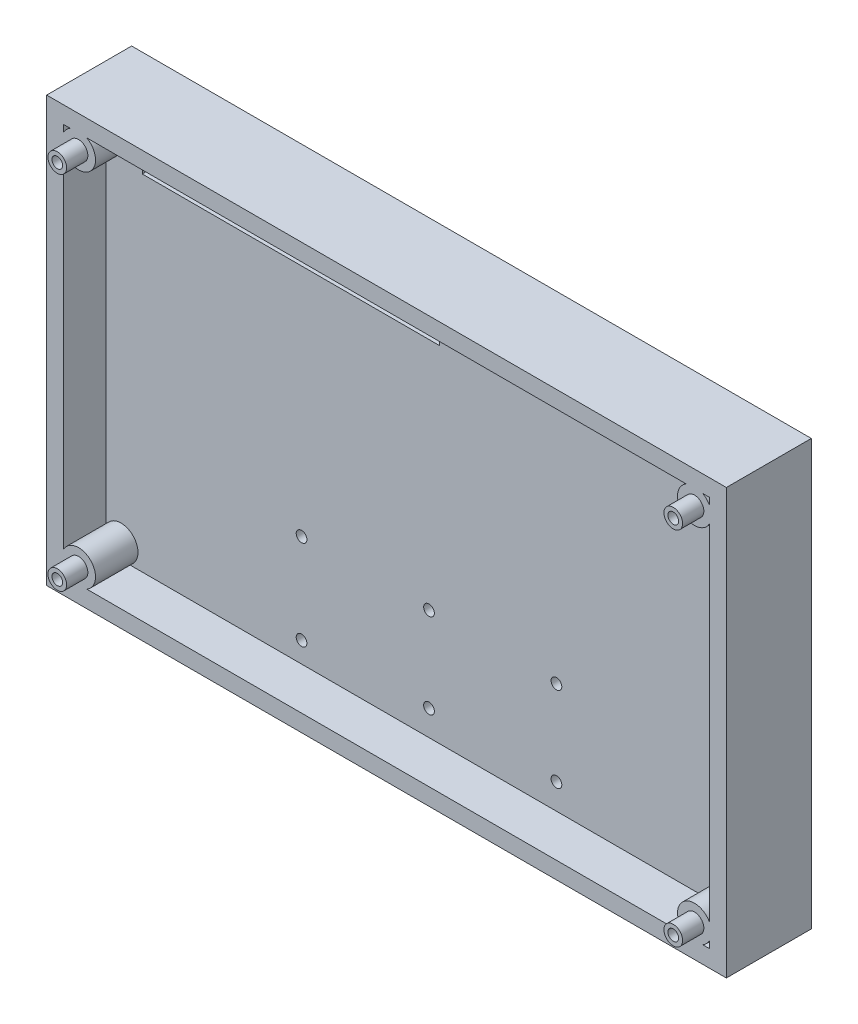
SolidWorks part; units mm, degrees
ref_plane "Front Plane" through (0, 0, 0) normal (0, 0, 1) x (1, 0, 0)
ref_plane "Top Plane" through (0, 0, 0) normal (0, 1, 0) x (1, 0, 0)
ref_plane "Right Plane" through (0, 0, 0) normal (1, 0, 0) x (0, 0, -1)
sketch "Sketch2" plane through (0, 0, 0) normal (0, 0, 1) x (1, 0, 0)
  line L1 (0, 0) -> (101.6, 0)
  line L2 (0, 0) -> (0, 63.5)
  line L3 (0, 63.5) -> (101.6, 63.5)
  line L4 (101.6, 0) -> (101.6, 63.5)
  dimension "D1" = 101.6
  dimension "D2" = 63.5
extrude "Boss-Extrude1" add sketch "Sketch2" along normal blind 6.35
sketch "Sketch3" plane through (0, 0, 6.35) normal (0, 0, 1) x (1, 0, 0)
  line L0 (0, 0) -> (101.6, 0) construction
  line L1 (0, 63.5) -> (0, 0) construction
  circle A0 centre (4.7625, 4.7625) radius 2.54
  circle A1 centre (96.8375, 4.7625) radius 2.54
  circle A2 centre (96.8375, 58.7375) radius 2.54
  circle A3 centre (4.7625, 58.7375) radius 2.54
  dimension "D1" = 92.075
  dimension "D3" = 0
  dimension "D4" = 53.975
  dimension "D5" = 4.7625
  dimension "D7" = 5.08
  dimension "D2" = 92.075
  dimension "D6" = 4.7625
extrude "Boss-Extrude2" add sketch "Sketch3" along normal blind 6.35
sketch "Sketch4" plane through (0, 0, 12.7) normal (0, 0, 1) x (1, 0, 0)
  circle A0 centre (4.7625, 58.7375) radius 1.397
  circle A1 centre (4.7625, 4.7625) radius 1.397
  circle A2 centre (96.8375, 58.7375) radius 1.397
  circle A3 centre (96.8375, 4.7625) radius 1.397
  dimension "D1" = 2.794
extrude "Boss-Extrude3" add sketch "Sketch4" along normal blind 3.175
hole_wizard "M2x0.4 Tapped Hole1" positions "Sketch5" profile "Sketch7" tap size "M2x0.4" standard "ANSI Metric"
sketch "Sketch5" plane through (0, 0, 15.875) normal (0, 0, 1) x (1, 0, 0)
  point P0 (4.7625, 58.7375)
  point P3 (4.7625, 4.7625)
  point P6 (96.8375, 58.7375)
  point P9 (96.8375, 4.7625)
sketch "Sketch7" plane through (4.7625, 58.7375, 15.875) normal (1, 0, 0) x (0, -1, 0)
  line L0 (0, 0) -> (0, 5.7447)
  line L1 (0, 5.7447) -> (0.8, 5.264)
  line L2 (0.8, 5.264) -> (0.8, 0)
  line L5 (0.8, 0) -> (0, 0)
  line L10 (0, 5.7447) -> (-0.8, 5.264) construction
  line L11 (0, -6.35) -> (0, 107.95) construction
  dimension "Tap Drill Dia." = 1.6
  dimension "Tap Drill Depth" = 5.264
  dimension "Drill Angle" = 118
cosmetic thread "Hole Thread1" parameters "D1"=4.064, "D2"=2
cosmetic thread "Hole Thread2" parameters "D1"=4.064, "D2"=2
cosmetic thread "Hole Thread3" parameters "D1"=4.064, "D2"=2
cosmetic thread "Hole Thread4" parameters "D1"=4.064, "D2"=2
sketch "Sketch8" plane through (0, 0, 6.35) normal (0, 0, 1) x (1, 0, 0)
  line L0 (101.6, 63.5) -> (0, 63.5) construction
  line L1 (7.9375, 60.4281) -> (52.3875, 60.4281)
  line L2 (7.9375, 60.4281) -> (7.9375, 54.0781)
  line L3 (7.9375, 54.0781) -> (52.3875, 54.0781)
  line L4 (52.3875, 60.4281) -> (52.3875, 54.0781)
  circle A0 centre (4.7625, 58.7375) radius 1.397 construction
  dimension "D1" = 44.45
  dimension "D2" = 6.35
  dimension "D3" = 3.175
  dimension "D4" = 3.0719
extrude "Cut-Extrude1" cut sketch "Sketch8" against normal blind 8.255
sketch3d "3DSketch1"
  line L0 (2.54, 2.54, 6.35) -> (99.06, 2.54, 6.35)
  line L1 (99.06, 2.54, 6.35) -> (99.06, 60.96, 6.35)
  line L2 (99.06, 60.96, 6.35) -> (2.54, 60.96, 6.35)
  line L3 (2.54, 60.96, 6.35) -> (2.54, 2.54, 6.35)
  line L4 (2.54, 2.54, 6.35) -> (99.06, 2.54, 6.35)
  line L5 (99.06, 2.54, 6.35) -> (99.06, 60.96, 6.35)
  line L6 (99.06, 60.96, 6.35) -> (2.54, 60.96, 6.35)
  line L7 (2.54, 60.96, 6.35) -> (2.54, 2.54, 6.35)
  line L9 (101.6, 0, 6.35) -> (101.6, 63.5, 6.35) construction
  line L10 (101.6, 63.5, 6.35) -> (0, 63.5, 6.35) construction
  line L11 (0, 0, 6.35) -> (101.6, 0, 6.35) construction
  line L12 (0, 63.5, 6.35) -> (0, 0, 6.35) construction
  line L13 (101.6, 0, 6.35) -> (101.6, 63.5, 6.35)
  line L14 (101.6, 63.5, 6.35) -> (0, 63.5, 6.35)
  line L15 (0, 0, 6.35) -> (101.6, 0, 6.35)
  line L16 (0, 63.5, 6.35) -> (0, 0, 6.35)
  dimension "D1" = 2.54
extrude "Boss-Extrude5" add sketch "3DSketch1" along direction (0, 0, -1) on the side against the normal blind 6.35
hole_wizard "M2x0.4 Tapped Hole2" positions "Sketch9" profile "Sketch10" tap size "M2x0.4" standard "ANSI Metric" end condition through all
sketch "Sketch9" plane through (0, 0, 0) normal (0, 0, -1) x (-1, 0, 0)
  line L0 (-101.6, 0) -> (-101.6, 63.5) construction
  line L1 (0, 0) -> (-101.6, 0) construction
  point P0 (-69.85, 19.05)
  point P2 (-50.8, 19.05)
  point P4 (-31.75, 19.05)
  point P6 (-69.85, 6.35)
  point P8 (-50.8, 6.35)
  point P10 (-31.75, 5.6205)
  dimension "D1" = 19.05
  dimension "D2" = 19.05
  dimension "D3" = 19.05
  dimension "D4" = 19.05
  dimension "D5" = 0
  dimension "D6" = 31.75
  dimension "D7" = 6.35
  dimension "D8" = 12.7
sketch "Sketch10" plane through (69.85, 19.05, 0) normal (1, 0, 0) x (0, 1, 0)
  line L0 (0, 0) -> (0, 15.875)
  line L1 (0, 15.875) -> (0.8, 15.875)
  line L2 (0.8, 15.875) -> (0.8, 0)
  line L5 (0.8, 0) -> (0, 0)
  line L11 (0, -6.35) -> (0, 107.95) construction
  dimension "Thru Tap Drill Dia." = 1.6
  dimension "Thru Tap Drill Depth" = 15.875
cosmetic thread "Hole Thread5" parameters "D2"=2
cosmetic thread "Hole Thread6" parameters "D2"=2
cosmetic thread "Hole Thread7" parameters "D2"=2
cosmetic thread "Hole Thread8" parameters "D2"=2
cosmetic thread "Hole Thread9" parameters "D2"=2
cosmetic thread "Hole Thread10" parameters "D2"=2
